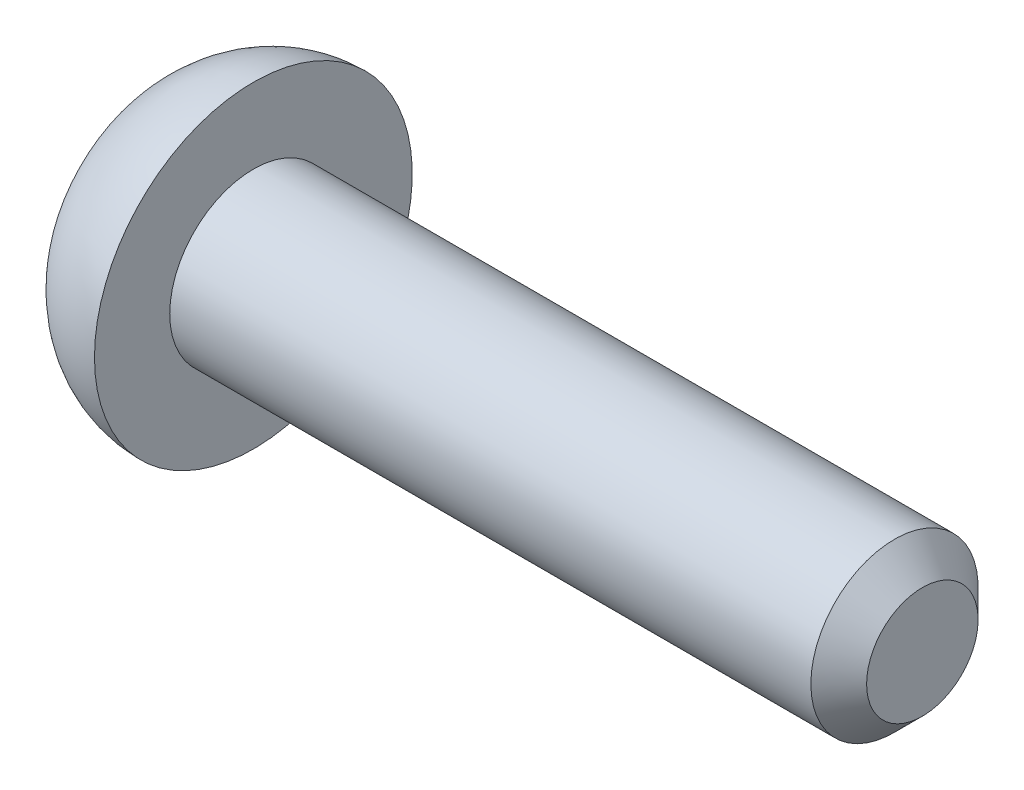
SolidWorks part; units mm, degrees
ref_plane "Front Plane" through (0, 0, 0) normal (0, 0, 1) x (1, 0, 0)
ref_plane "Top Plane" through (0, 0, 0) normal (0, 1, 0) x (1, 0, 0)
ref_plane "Right Plane" through (0, 0, 0) normal (1, 0, 0) x (0, 0, -1)
sketch "Sketch2" plane through (0, 0, 0) normal (0, 1, 0) x (1, 0, 0)
  line L0 (0, 0) -> (0, 1.5)
  line L1 (0, -55) -> (0, 55) construction
  line L2 (0, 1.5) -> (-12, 1.5)
  line L3 (-12, 1.5) -> (-12, 0) construction
  line L4 (-55, 0) -> (55, 0) construction
  line L5 (-13.65, 2.049) -> (-13.65, 0)
  line L6 (-13.65, 0) -> (0, 0)
  line L7 (-12, 2.85) -> (-12, 1.5)
  arc A0 (-13.65, 2.049) -> (-12, 2.85) centre (-12, 0.75) cw
  dimension "D2" = 12
  dimension "D3" = 2.85
  dimension "D1" = 1.65
  dimension "D4" = 1.5
revolve "Revolve1" add sketch "Sketch2" angle 360 about L6
chamfer "Chamfer1" distance 0.5 angle 45 1 edges at (0, 0, 1.5)
sketch "Sketch4" plane through (-13.65, 0, 0) normal (-1, 0, 0) x (0, 0, 1)
  line L1 (0.8389, 1.453) -> (-0.8389, 1.453) construction
  line L2 (-0.8389, 1.453) -> (-1.6778, 0) construction
  line L3 (-1.6778, 0) -> (-0.8389, -1.453) construction
  line L4 (-0.8389, -1.453) -> (0.8389, -1.453) construction
  line L5 (0.8389, -1.453) -> (1.6778, 0) construction
  line L6 (1.6778, 0) -> (0.8389, 1.453) construction
  circle A0 centre (0, 0) radius 1.453 construction
  arc A1 (-1.342, 0.0907) -> (-0.7496, 1.1169) centre (-1.7745, 1.0245) ccw
  arc A2 (-0.5924, 1.2076) -> (0.5924, 1.2076) centre (0, 2.049) ccw
  arc A3 (0.7496, 1.1169) -> (1.342, 0.0907) centre (1.7745, 1.0245) ccw
  arc A4 (1.342, -0.0907) -> (0.7496, -1.1169) centre (1.7745, -1.0245) ccw
  arc A5 (-0.5924, -1.2076) -> (0.5924, -1.2076) centre (0, -2.049) cw
  arc A6 (-0.7496, -1.1169) -> (-1.342, -0.0907) centre (-1.7745, -1.0245) ccw
  circle A7 centre (0, 0) radius 2.049 construction
  arc A8 (0.7496, 1.1169) -> (0.5924, 1.2076) centre (0.65, 1.1258) ccw
  arc A9 (1.342, -0.0907) -> (1.342, 0.0907) centre (1.3, 0) ccw
  arc A10 (0.7496, -1.1169) -> (0.5924, -1.2076) centre (0.65, -1.1258) cw
  arc A11 (-0.7496, -1.1169) -> (-0.5924, -1.2076) centre (-0.65, -1.1258) ccw
  arc A12 (-1.342, 0.0907) -> (-1.342, -0.0907) centre (-1.3, 0) ccw
  arc A13 (-0.7496, 1.1169) -> (-0.5924, 1.2076) centre (-0.65, 1.1258) cw
  circle A14 centre (0, 0) radius 2.049 construction
  point P40 (2.049, 0)
  dimension "D1" = 0.1
  dimension "D2" = 2.6
extrude "Cut-Extrude1" cut sketch "Sketch4" against normal blind 1
equation "\"d1\"= 3"
equation "\"l\"= 12"
equation "\"d2\"= 5.7"
equation "\"t\"= 1"
equation "\"k\"=1.65"
equation "\"A\"=2.8"
equation "\"D3@Sketch2\"=\"d2\" / 2"
equation "\"D1@Sketch2\"= \"k\""
equation "\"D4@Sketch2\"=\"d1\" / 2"
equation "\"D2@Sketch4\"= \"A\" - 2 * \"D1@Sketch4\""
equation "\"D1@Cut-Extrude1\"= \"t\""
equation "\"D2@Sketch2\"=\"l\""
